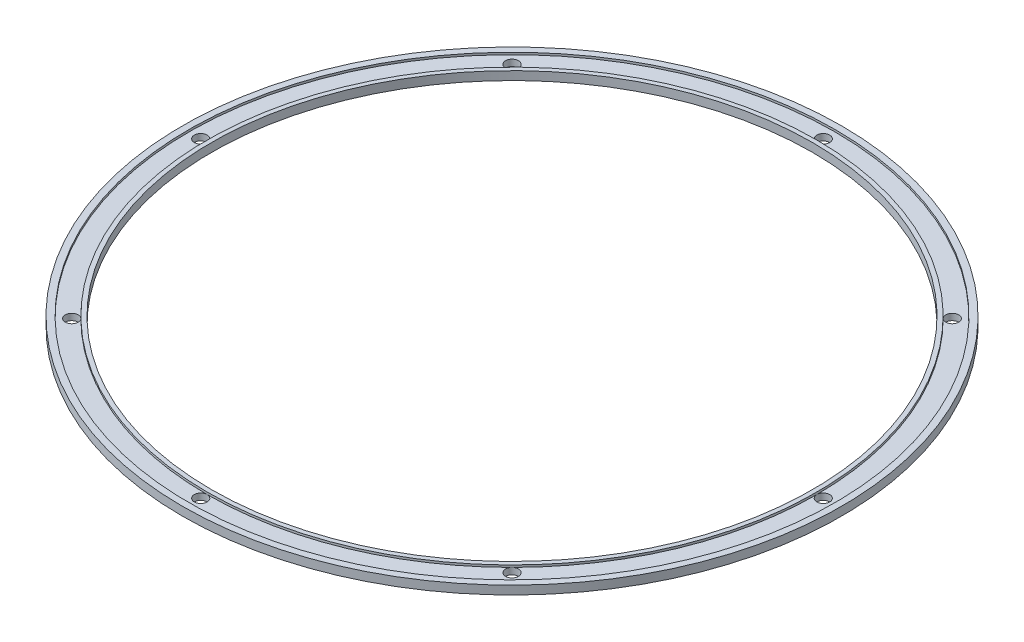
SolidWorks part; units mm, degrees
material "6061-T6 (SS)"
ref_plane "前视基准面" through (0, 0, 0) normal (0, 0, 1) x (1, 0, 0)
ref_plane "上视基准面" through (0, 0, 0) normal (0, 1, 0) x (1, 0, 0)
ref_plane "右视基准面" through (0, 0, 0) normal (1, 0, 0) x (0, 0, -1)
sketch "草图1" plane through (0, 0, 0) normal (0, 0, 1) x (1, 0, 0)
  line L0 (0, 112.5721) -> (0, -113.9925) construction
  line L1 (-146.7256, 0) -> (148.4442, 0) construction
  line L2 (70, 0) -> (76.75, 0)
  line L3 (76.75, 0) -> (76.75, 2)
  line L4 (76.75, 2) -> (75.25, 2)
  line L5 (75.25, 2) -> (75.25, 1.5)
  line L6 (75.25, 1.5) -> (71, 1.5)
  line L7 (71, 1.5) -> (71, 2)
  line L8 (71, 2) -> (70, 2)
  line L9 (70, 2) -> (70, 0)
  point P9 (76, 2)
  dimension "D1" = 140
  dimension "D2" = 153.5
  dimension "D3" = 1
  dimension "D4" = 150.5
  dimension "D5" = 0.5
  dimension "D6" = 2
revolve "旋转1" add sketch "草图1" angle 360 about L0
sketch "草图2" plane through (0, 1.5, 0) normal (0, 1, 0) x (1, 0, 0)
  circle A0 centre (0, 0) radius 72.5 construction
  circle A1 centre (0, 72.5) radius 1.5
  circle A2 centre (51.2652, 51.2652) radius 1.5
  circle A3 centre (72.5, 0) radius 1.5
  circle A4 centre (51.2652, -51.2652) radius 1.5
  circle A5 centre (0, -72.5) radius 1.5
  circle A6 centre (-51.2652, -51.2652) radius 1.5
  circle A7 centre (-72.5, 0) radius 1.5
  circle A8 centre (-51.2652, 51.2652) radius 1.5
  point P21 (0, 0)
  dimension "D1" = 145
  dimension "D2" = 3
  dimension "D3" = 8
extrude "切除-拉伸1" cut sketch "草图2" against normal through all
move or copy body "实体-移动/复制1" bodies to move or copy 107
